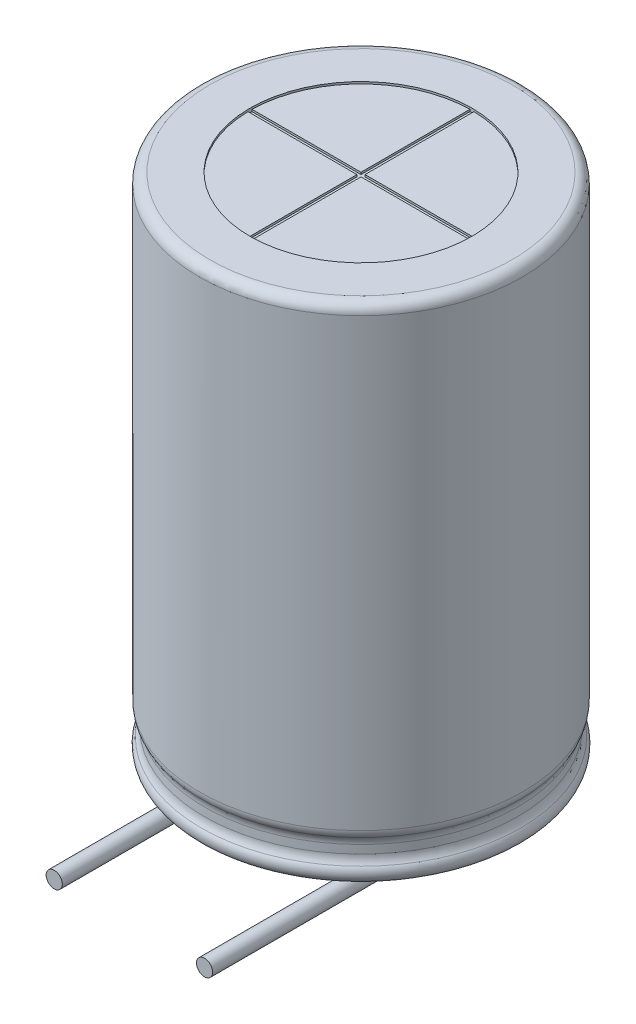
SolidWorks part; units mm, degrees
ref_plane "Front Plane" through (0, 0, 0) normal (0, 0, 1) x (1, 0, 0)
ref_plane "Top Plane" through (0, 0, 0) normal (0, 1, 0) x (1, 0, 0)
ref_plane "Right Plane" through (0, 0, 0) normal (1, 0, 0) x (0, 0, -1)
sketch "Sketch1" plane through (0, 0, 0) normal (0, 0, 1) x (1, 0, 0)
  line L0 (8, 25) -> (0, 25)
  line L1 (0, 25) -> (0, 0)
  line L2 (0, 0) -> (8, 0)
  line L3 (7.7604, 1.2326) -> (7.7604, 1.6424)
  line L4 (8, 2.4076) -> (8, 25)
  line L5 (0, 25) -> (0, 0) construction
  arc A0 (8, 0) -> (7.9281, 0.789) centre (7.4249, 0.3453) ccw
  arc A1 (7.9281, 0.789) -> (7.7604, 1.2326) centre (8.4312, 1.2326) cw
  arc A2 (7.7604, 1.6424) -> (7.8802, 2.025) centre (8.4312, 1.6424) cw
  arc A3 (7.8802, 2.025) -> (8, 2.4076) centre (7.3292, 2.4076) ccw
  dimension "D1" = 25
  dimension "D2" = 8
revolve "Revolve1" add sketch "Sketch1" angle 360 about L5
sketch "Sketch2" plane through (0, 25, 0) normal (0, 1, 0) x (-1, 0, 0)
  circle A0 centre (0, 0) radius 5.5
  dimension "D1" = 11
extrude "Cut-Extrude1" cut sketch "Sketch2" against normal blind 0.1
sketch "Sketch3" plane through (0, 24.9, 0) normal (0, 1, 0) x (-1, 0, 0)
  line L0 (-5.4991, -0.1) -> (-0.1, -0.1)
  line L1 (-0.1, -0.1) -> (-0.1, -5.4991)
  line L2 (-0.1, 5.4991) -> (-0.1, 0.1)
  line L3 (-0.1, 0.1) -> (-5.4991, 0.1)
  line L4 (5.4991, 0.1) -> (0.1, 0.1)
  line L5 (0.1, 0.1) -> (0.1, 5.4991)
  line L6 (0.1, -5.4991) -> (0.1, -0.1)
  line L7 (0.1, -0.1) -> (5.4991, -0.1)
  line L9 (0, 6.2081) -> (0, -6.5499) construction
  line L10 (6.8771, 0) -> (-11.2847, 0) construction
  circle A0 centre (0, 0) radius 5.5 construction
  arc A1 (-5.5, 0) -> (-5.4991, -0.1) centre (0, 0) ccw
  arc A2 (-0.1, -5.4991) -> (0, -5.5) centre (0, 0) ccw
  arc A3 (0, 5.5) -> (-0.1, 5.4991) centre (0, 0) ccw
  arc A4 (-5.4991, 0.1) -> (-5.5, 0) centre (0, 0) ccw
  arc A5 (5.5, 0) -> (5.4991, 0.1) centre (0, 0) ccw
  arc A6 (0.1, 5.4991) -> (0, 5.5) centre (0, 0) ccw
  arc A7 (0, -5.5) -> (0.1, -5.4991) centre (0, 0) ccw
  arc A8 (5.4991, -0.1) -> (5.5, 0) centre (0, 0) ccw
  dimension "D1" = 0.1
  dimension "D2" = 0.1
  dimension "D3" = 4
extrude "Cut-Extrude2" cut sketch "Sketch3" against normal blind 0.1
sketch "Croquis4" plane through (0, 0, 0) normal (0, -1, 0) x (1, 0, 0)
  circle A0 centre (0, 0) radius 5.5
  dimension "D1" = 11
extrude "Cortar-Extruir1" cut sketch "Croquis4" against normal blind 0.25
ref_plane "Plano1" through (3.75, 0, 0) normal (1, 0, 0) x (0, 0, -1)
sketch "Croquis2" plane through (3.75, 0, 0) normal (1, 0, 0) x (0, 0, -1)
  line L0 (0, 0.25) -> (0, 0)
  line L1 (-1.5, -1.5) -> (-11.5, -1.5)
  arc A0 (0, 0) -> (-1.5, -1.5) centre (-1.5, 0) cw
  point P8 (0, 0)
  point P9 (0, 0)
  point P10 (0, 0)
  point P11 (0, 0)
  point P12 (0, 0)
  point P13 (0, 0)
  point P14 (0, 0)
  point P15 (0, 0)
  point P16 (0, 0.25)
  dimension "D1" = 1.5
  dimension "D2" = 0.25
  dimension "D3" = 10
sketch "Croquis8" plane through (0, 0.25, 0) normal (0, -1, 0) x (1, 0, 0)
  line L0 (3.75, 0) -> (3.75, 1.5) construction
  circle A0 centre (3.75, 0) radius 0.4
  point P4 (0, 0)
  point P5 (0, 0)
  dimension "D1" = 0.8
fillet "Fillet1" radius 0.5 2 edges at (8, 25, 0) (8, 0, 0)
ref_plane "Plano2" through (-3.75, 0, 0) normal (1, 0, 0) x (0, 0, -1)
sketch "Croquis6" plane through (-3.75, 0, 0) normal (1, 0, 0) x (0, 0, -1)
  line L0 (0.0523, 0.25) -> (0.0523, 0)
  line L1 (-1.4477, -1.5) -> (-11.4477, -1.5)
  line L2 (-5.5, 0.25) -> (5.5, 0.25) construction
  arc A0 (0.0523, 0) -> (-1.4477, -1.5) centre (-1.4477, 0) cw
  point P6 (0, 0)
  point P7 (0, 0)
  point P8 (0, 0)
  point P9 (0, 0)
  point P10 (0, 0)
  point P11 (0, 0)
  point P14 (0, 0)
  point P15 (0, 0)
  point P16 (0.0523, 0.25)
  dimension "D1" = 1.5
  dimension "D2" = 0.25
  dimension "D3" = 10
sketch "Croquis7" plane through (0, 0.25, 0) normal (0, -1, 0) x (1, 0, 0)
  line L0 (-3.75, -0.0523) -> (-3.75, 1.4477) construction
  circle A0 centre (-3.75, -0.0523) radius 0.4
  point P4 (-3.75, 0)
  point P5 (0, 0)
  point P6 (0, 0)
  point P8 (-3.75, -0.0523)
  point P9 (0, 0)
  dimension "D1" = 0.8
sweep "Barrer6" add profiles "Croquis8" path "Croquis2"
sweep "Barrer7" add profiles "Croquis7" path "Croquis6"
